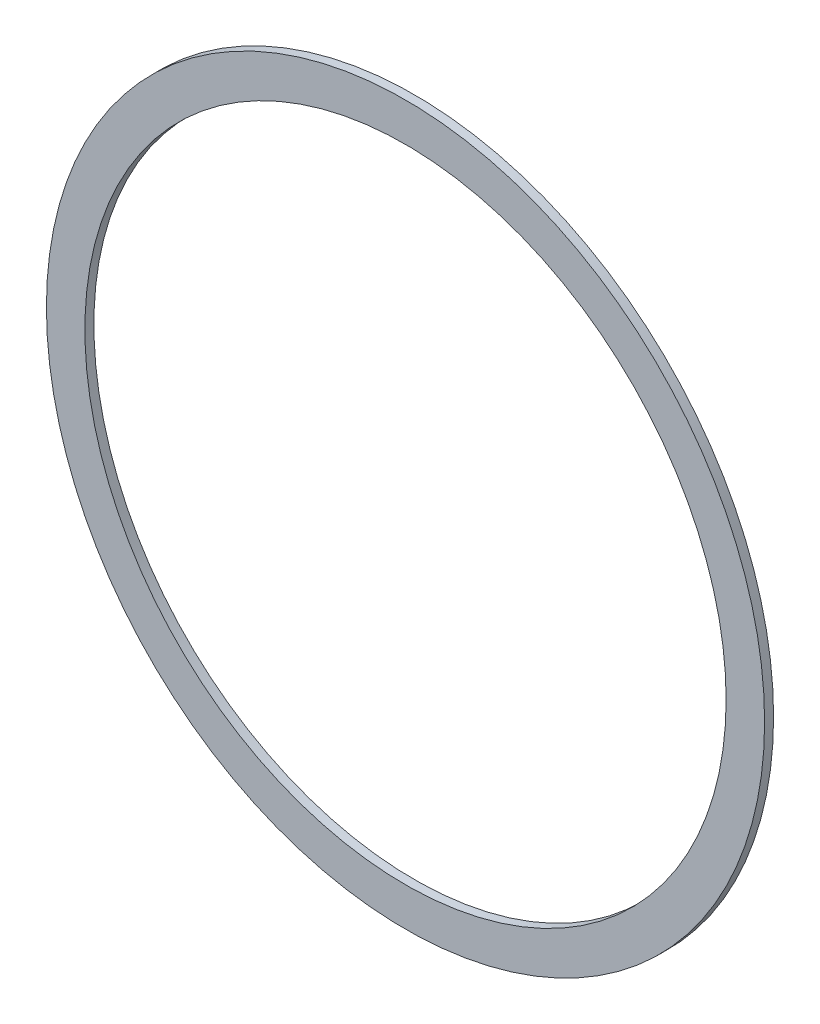
SolidWorks part; units mm, degrees
ref_plane "Спереди" through (0, 0, 0) normal (0, 0, 1) x (1, 0, 0)
ref_plane "Сверху" through (0, 0, 0) normal (0, 1, 0) x (1, 0, 0)
ref_plane "Справа" through (0, 0, 0) normal (1, 0, 0) x (0, 0, -1)
sketch "Эскиз1" plane through (0, 0, 0) normal (1, 0, 0) x (0, 0, -1)
  line L0 (0, 12.5) -> (0, 14)
  line L1 (0, 14) -> (0.35, 14)
  line L2 (0.35, 14) -> (0.35, 12.5)
  line L3 (0.35, 12.5) -> (0, 12.5)
  line L4 (0, 0) -> (3.1385, 0) construction
  dimension "D1" = 25
  dimension "D2" = 1.5
  dimension "D3" = 0.35
revolve "Повернуть1" add sketch "Эскиз1" angle 360 about L4
